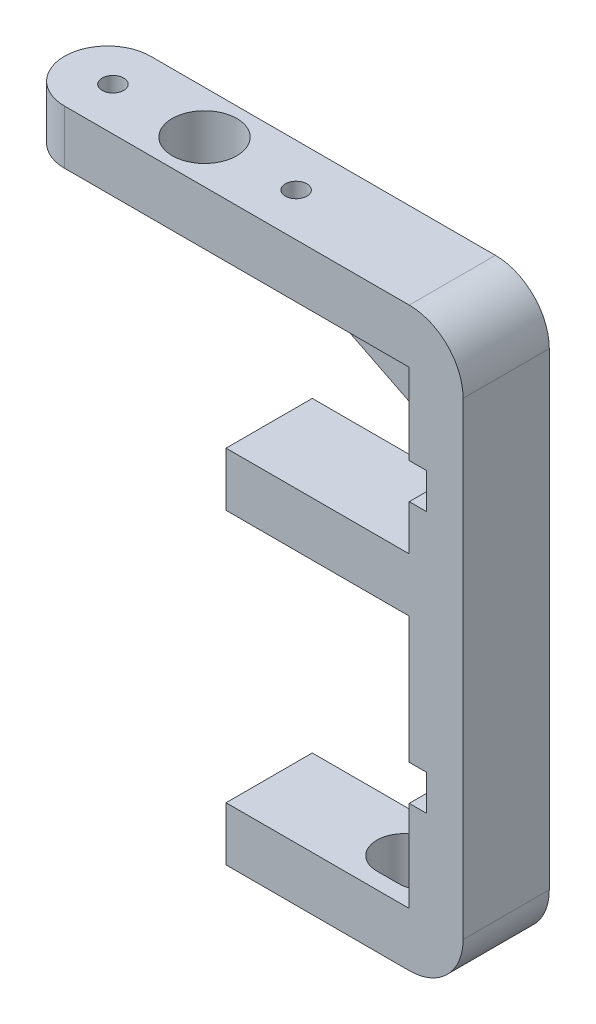
SolidWorks part; units mm, degrees
material "Plain Carbon Steel"
ref_plane "Front Plane" through (0, 0, 0) normal (0, 0, 1) x (1, 0, 0)
ref_plane "Top Plane" through (0, 0, 0) normal (0, 1, 0) x (1, 0, 0)
ref_plane "Right Plane" through (0, 0, 0) normal (1, 0, 0) x (0, 0, -1)
sketch "Sketch1" plane through (0, 0, 0) normal (0, 0, 1) x (1, 0, 0)
  line L0 (-185, 0) -> (0, 0)
  line L1 (0, 0) -> (0, -267.5)
  line L2 (0, -267.5) -> (-110, -267.5)
  line L3 (-110, -125) -> (-25, -125)
  line L4 (-185, 0) -> (-185, -25)
  line L5 (-185, -25) -> (-25, -25)
  line L6 (-25, -25) -> (-25, -100)
  line L7 (-25, -100) -> (-110, -100)
  line L8 (-110, -100) -> (-110, -125)
  line L9 (-25, -125) -> (-25, -242.5)
  line L10 (-25, -242.5) -> (-110, -242.5)
  line L11 (-110, -242.5) -> (-110, -267.5)
  line L12 (-25, -125) -> (0, -125) construction
  dimension "D1" = 25
  dimension "D2" = 117.5
  dimension "D3" = 75
  dimension "D4" = 185
  dimension "D5" = 110
extrude "Boss-Extrude1" add sketch "Sketch1" along normal mid plane 40
sketch "Sketch2" plane through (0, 0, 0) normal (0, 1, 0) x (1, 0, 0)
  line L0 (-185, -20) -> (-185, 20) construction
  line L1 (-185, 20) -> (-185, -20)
  arc A0 (-185, -20) -> (-185, 20) centre (-185, 0) cw
extrude "Boss-Extrude2" add sketch "Sketch2" against normal up to surface (25 mm away) up to face at (-105, -25, 0)
sketch "Sketch3" plane through (0, 0, 0) normal (0, 1, 0) x (1, 0, 0)
  line L0 (-140, 15) -> (-140, -15) construction
  circle A0 centre (-140, 0) radius 15
  arc A1 (-185, 20) -> (-185, -20) centre (-185, 0) ccw construction
  circle A2 centre (-182.5, 0) radius 5
  circle A3 centre (-97.5, 0) radius 5
  point P6 (-205, 0)
  dimension "D1" = 85
  dimension "D2" = 30
  dimension "D3" = 10
  dimension "D4" = 65
extrude "Cut-Extrude1" cut sketch "Sketch3" against normal up to surface (25 mm away) up to face at (-110, -25, 0)
fillet "Fillet1" radius 25 2 edges at (0, -267.5, 0) (0, 0, 0)
sketch "Sketch4" plane through (-110, 0, 0) normal (-1, 0, 0) x (0, 0, 1)
  line L0 (20, -242.5) -> (-20, -242.5) construction
  line L1 (-20, -183.75) -> (20, -183.75) construction
  line L2 (-20, -125) -> (-20, -242.5) construction
  line L3 (20, -125) -> (20, -242.5) construction
  line L4 (-20, -242.5) -> (-20, -267.5) construction
  line L5 (20, -267.5) -> (-20, -267.5) construction
  circle A0 centre (0, -251.225) radius 6
  circle A1 centre (0, -116.275) radius 6
  point P4 (0, -242.5)
  dimension "D1" = 12
  dimension "D2" = 134.95
extrude "Cut-Extrude2" cut sketch "Sketch4" against normal blind 40
sketch "Sketch5" plane through (-25, 0, 0) normal (-1, 0, 0) x (0, 0, 1)
  line L0 (-20, -25) -> (-20, -100) construction
  line L1 (-20, -62.5) -> (20, -62.5)
  line L2 (-20, -62.5) -> (-20, -79)
  line L3 (-20, -79) -> (20, -79)
  line L4 (20, -62.5) -> (20, -79)
  line L5 (20, -25) -> (20, -100) construction
  line L6 (-20, -125) -> (-20, -242.5) construction
  line L7 (-20, -183.75) -> (20, -183.75)
  line L8 (-20, -183.75) -> (-20, -200.25)
  line L9 (-20, -200.25) -> (20, -200.25)
  line L10 (20, -183.75) -> (20, -200.25)
  line L11 (20, -125) -> (20, -242.5) construction
  line L12 (20, -100) -> (-20, -100) construction
  line L13 (20, -242.5) -> (-20, -242.5) construction
  dimension "D1" = 21
  dimension "D2" = 42.25
  dimension "D3" = 16.5
extrude "Cut-Extrude3" cut sketch "Sketch5" against normal blind 8
sketch "Sketch6" plane through (0, 0, 0) normal (0, 0, 1) x (1, 0, 0)
  line L0 (-75, -25) -> (-25, -50)
  line L1 (-185, -25) -> (-25, -25) construction
  line L2 (-25, -25) -> (-25, -62.5) construction
  dimension "D1" = 25
  dimension "D2" = 50
rib "Rib1" sketch "Sketch6" sketch "Sketch6" thickness 25 extrusion direction parallel to sketch draft on no parameters "D1"=25
sketch "Sketch7" plane through (0, -267.5, 0) normal (0, -1, 0) x (1, 0, 0)
  line L0 (-47.5, 0) -> (-37.5, 0) construction
  line L1 (-47.5, 12.5) -> (-37.5, 12.5)
  line L2 (-47.5, -12.5) -> (-37.5, -12.5)
  line L3 (-110, 20) -> (-110, -20) construction
  arc A0 (-47.5, 12.5) -> (-47.5, -12.5) centre (-47.5, 0) ccw
  arc A1 (-37.5, -12.5) -> (-37.5, 12.5) centre (-37.5, 0) ccw
  point P3 (-42.5, 0)
  dimension "D1" = 62.5
  dimension "D2" = 10
  dimension "D3" = 25
extrude "Cut-Extrude4" cut sketch "Sketch7" against normal up to surface (25 mm away) up to face at (-67.5, -242.5, 0)
sketch "Sketch8" plane through (0, -125, 0) normal (0, -1, 0) x (1, 0, 0)
  line L0 (0, 0) -> (-205, 0) construction
  line L1 (-25, 0) -> (-25, 20) construction
  line L2 (-47, 12) -> (-38, 12)
  line L3 (-47, 12) -> (-47, -12)
  line L4 (-47, -12) -> (-38, -12)
  line L5 (-38, 12) -> (-38, -12)
  line L6 (-47, 12) -> (-38, -12) construction
  line L7 (-47, -12) -> (-38, 12) construction
  arc A0 (-185, 20) -> (-185, -20) centre (-185, 0) ccw construction
  point P6 (-42.5, 0)
  dimension "D1" = 13
  dimension "D2" = 24
  dimension "D3" = 9
extrude "Cut-Extrude5" cut sketch "Sketch8" against normal blind 8
